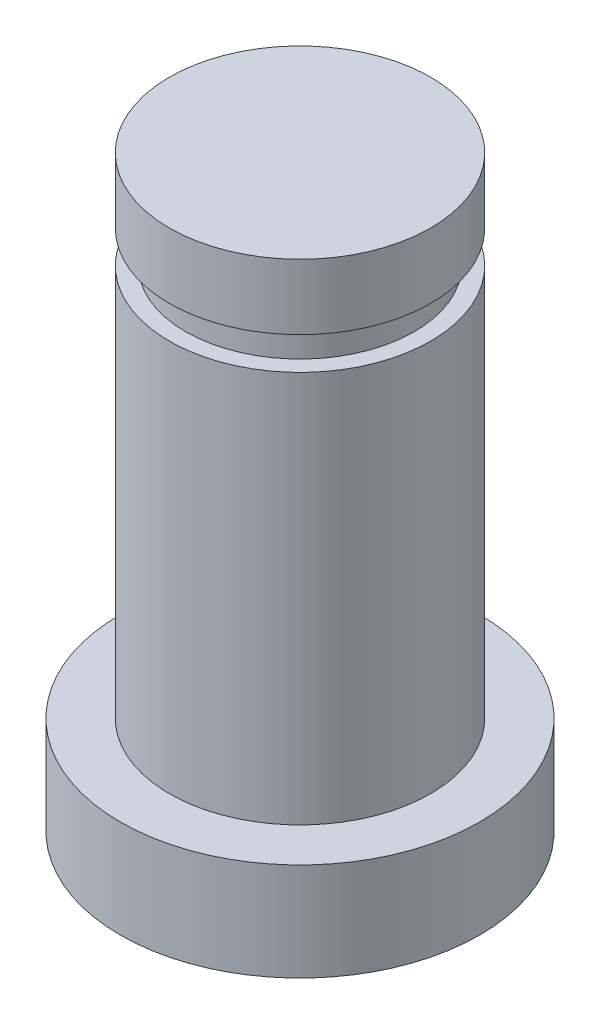
SolidWorks part; units mm, degrees
ref_plane "Front Plane" through (0, 0, 0) normal (0, 0, 1) x (1, 0, 0)
ref_plane "Top Plane" through (0, 0, 0) normal (0, 1, 0) x (1, 0, 0)
ref_plane "Right Plane" through (0, 0, 0) normal (1, 0, 0) x (0, 0, -1)
sketch "Sketch1" plane through (0, 0, 0) normal (0, 1, 0) x (1, 0, 0)
  circle A0 centre (0, 0) radius 5.08
  dimension "D1" = 10.16
extrude "Boss-Extrude1" add sketch "Sketch1" along normal blind 15.24
sketch "Sketch4" plane through (0, 15.24, 0) normal (0, 1, 0) x (1, 0, 0)
  circle A0 centre (0, 0) radius 4.445
  dimension "D1" = 8.89
extrude "Boss-Extrude4" add sketch "Sketch4" along normal blind 1.27
sketch "Sketch5" plane through (0, 16.51, 0) normal (0, 1, 0) x (1, 0, 0)
  circle A0 centre (0, 0) radius 5.08
extrude "Boss-Extrude5" add sketch "Sketch5" along normal blind 2.54
sketch "Sketch6" plane through (0, 0, 0) normal (0, -1, 0) x (1, 0, 0)
  circle A0 centre (0, 0) radius 6.985
  dimension "D1" = 13.97
extrude "Boss-Extrude8" add sketch "Sketch6" along normal blind 3.81
